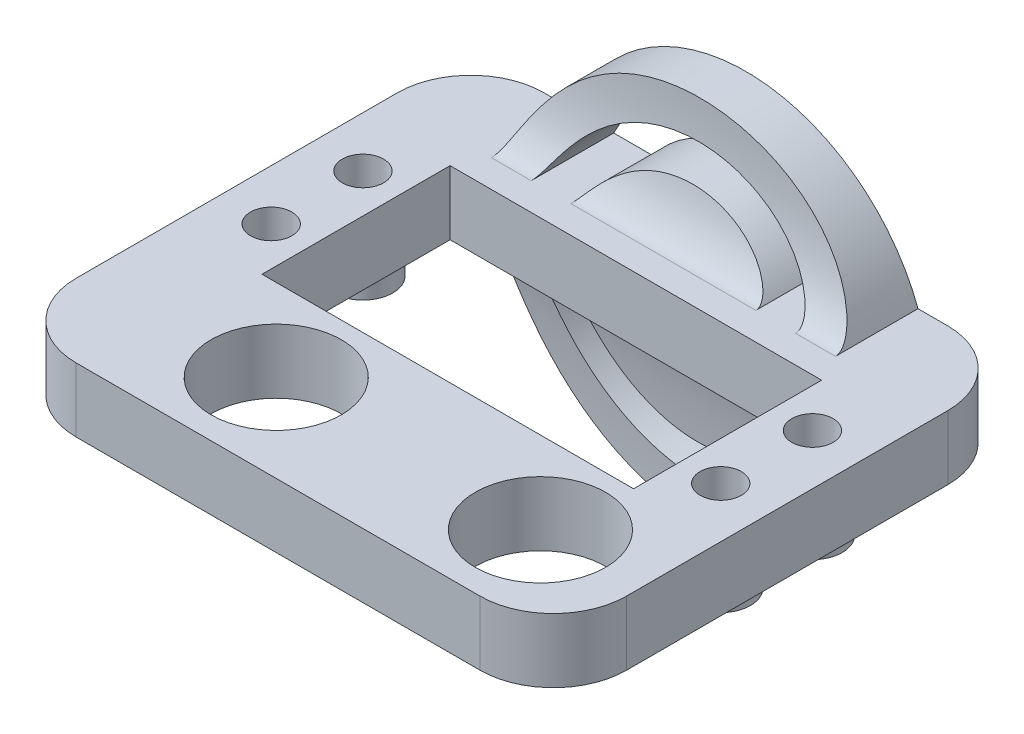
SolidWorks part; units mm, degrees
other "Markup1"
sketch "Sketch5" plane through (30, -20.02, -30) normal (0.0767, -0.0129, -0.997) x (0.9182, -0.3888, 0.0757)
ref_plane "Front Plane" through (0, 0, 0) normal (0, 0, 1) x (1, 0, 0)
ref_plane "Top Plane" through (0, 0, 0) normal (0, 1, 0) x (1, 0, 0)
ref_plane "Right Plane" through (0, 0, 0) normal (1, 0, 0) x (0, 0, -1)
sketch "Sketch1" plane through (0, 0, 0) normal (0, 1, 0) x (1, 0, 0)
  line L0 (-9.75, 7.75) -> (-9.75, -11.45) construction
  line L1 (-30, -21) -> (30, -21)
  line L2 (-30, -21) -> (-30, 21)
  line L3 (-30, 21) -> (30, 21)
  line L4 (30, -21) -> (30, 21)
  line L5 (0, 21) -> (0, -21) construction
  line L6 (-30, 0) -> (30, 0) construction
  line L7 (-20.25, -2.5) -> (20.25, -2.5)
  line L8 (-20.25, -2.5) -> (-20.25, 18)
  line L9 (-20.25, 18) -> (20.25, 18)
  line L10 (20.25, -2.5) -> (20.25, 18)
  line L11 (0, 18) -> (0, -2.5) construction
  line L12 (-20.25, 7.75) -> (20.25, 7.75) construction
  line L13 (-9.75, -11.45) -> (19.05, -11.45) construction
  line L14 (24.5, 12.75) -> (24.5, 2.75) construction
  line L15 (20.25, 7.75) -> (30, 7.75) construction
  circle A0 centre (-9.75, -11.45) radius 7.1
  circle A1 centre (19.05, -11.45) radius 7.1
  circle A2 centre (24.5, 12.75) radius 2.25
  circle A3 centre (24.5, 2.75) radius 2.25
  circle A4 centre (-24.5, 2.75) radius 2.25
  circle A5 centre (-24.5, 12.75) radius 2.25
  point P0 (0, 0)
  point P4 (0, 7.75)
  point P17 (24.5, 7.75)
  dimension "D7" = 4.5
  dimension "D8" = 4.5
  dimension "D12" = 14.2
  dimension "D13" = 14.2
  dimension "D1" = 40.5
  dimension "D2" = 20.5
  dimension "D3" = 3
  dimension "D4" = 19.2
  dimension "D5" = 28.8
  dimension "D6" = 60
  dimension "D9" = 10
  dimension "D10" = 24.5
  dimension "D11" = 42
  dimension "D14" = 30
extrude "Boss-Extrude1" add sketch "Sketch1" along normal blind 7
sketch "Sketch2" plane through (0, 0, 0) normal (0, -1, 0) x (1, 0, 0)
  line L5 (0, -1000) -> (0, 49000) construction
  circle A0 centre (24.5, -2.75) radius 3.25
  circle A1 centre (24.5, -12.75) radius 3.25
  circle A2 centre (24.5, -12.75) radius 2.25 construction
  circle A3 centre (24.5, -2.75) radius 2.25 construction
  circle A4 centre (24.5, -12.75) radius 2.25
  circle A5 centre (24.5, -2.75) radius 2.25
  circle A6 centre (-24.5, -12.75) radius 3.25
  circle A7 centre (-24.5, -12.75) radius 2.25
  circle A8 centre (-24.5, -2.75) radius 3.25
  circle A9 centre (-24.5, -2.75) radius 2.25
  dimension "D1" = 6.5
  dimension "D2" = 6.5
extrude "Boss-Extrude2" add sketch "Sketch2" along normal blind 2.9
sketch "Sketch3" plane through (0, 0, -21) normal (0, 0, -1) x (-1, 0, 0)
  line L4 (-30, 0) -> (30, 0)
  line L5 (30, 0) -> (30, 7)
  line L6 (30, 7) -> (-30, 7)
  line L7 (-30, 7) -> (-30, 0)
  line L8 (-30, 0) -> (30, 0)
  line L9 (30, 0) -> (30, 7)
  line L10 (30, 7) -> (-30, 7)
  line L11 (-30, 7) -> (-30, 0)
  circle A0 centre (0, 0) radius 20.02
  circle A1 centre (0, 0) radius 16.02
  circle A2 centre (0, 0) radius 12.27
  dimension "D2" = 4
  dimension "D3" = 24.54
  dimension "D4" = 3.75
  dimension "D1" = 0
extrude "Boss-Extrude3" add sketch "Sketch3" along normal blind 9
sketch "Sketch4" plane through (-30, 0, 0) normal (-1, 0, 0) x (0, 0, 1)
  line L0 (-21, 20.02) -> (-30, 20.02) construction
  line L1 (-25, 20.02) -> (-25, -20.02) construction
  line L4 (-30, 7) -> (21, 7) construction
  line L7 (-30, -20.02) -> (-21, -20.02) construction
  line L8 (-30, 20.02) -> (-30, 7) construction
  ellipse E0 centre (-21, 20.02) end of major axis (-21, 7) minor radius 4
  ellipse E1 centre (-21, -20.02) end of major axis (-21, 0) minor radius 4
  dimension "D1" = 5
extrude "Cut-Extrude1" cut sketch "Sketch4" against normal through all
fillet "Fillet1" radius 8 4 edges at (-30, 3.5, 21) (30, 3.5, 21) (30, 3.5, -30) (-30, 3.5, -30)
